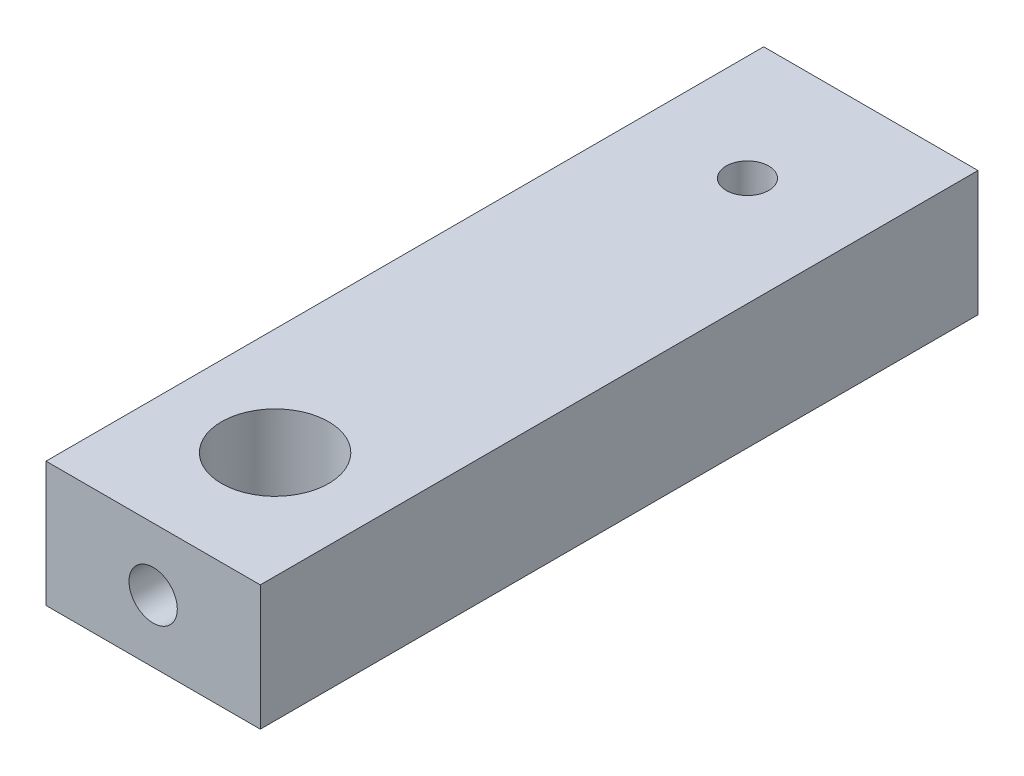
SolidWorks part; units mm, degrees
ref_plane "Front" through (0, 0, 0) normal (0, 0, 1) x (1, 0, 0)
ref_plane "Top" through (0, 0, 0) normal (0, 1, 0) x (1, 0, 0)
ref_plane "Right" through (0, 0, 0) normal (1, 0, 0) x (0, 0, -1)
sketch "Sketch9" plane through (0, 0, 0) normal (0, 1, 0) x (1, 0, 0)
  line L1 (-6, -20.095) -> (6, -20.095)
  line L2 (-6, -20.095) -> (-6, 20.095)
  line L3 (-6, 20.095) -> (6, 20.095)
  line L4 (6, -20.095) -> (6, 20.095)
  line L5 (-6, -20.095) -> (6, 20.095) construction
  line L6 (-6, 20.095) -> (6, -20.095) construction
  point P0 (0, 0)
  dimension "D1" = 12
  dimension "D2" = 40.19
extrude "Extrude3" add sketch "Sketch9" along normal blind 7
hole_wizard "3/32 (0.09375) Diameter Hole1" positions "3DSketch1" profile "Sketch10" hole size "3/32" standard "Ansi Inch"
sketch3d "3DSketch1"
  point P0 (-0.0811, 7, -13.2663)
  dimension "D1" = 15
sketch "Sketch10" plane through (-0.0811, 7, -13.2663) normal (1, 0, 0) x (0, 0, 1)
  line L0 (0, 0) -> (0, 10.7154)
  line L1 (0, 10.7154) -> (1.1906, 10)
  line L2 (1.1906, 10) -> (1.1906, 0)
  line L5 (1.1906, 0) -> (0, 0)
  line L10 (0, 10.7154) -> (-1.1906, 10) construction
  line L11 (0, -6.35) -> (0, 107.95) construction
  dimension "Hole Dia." = 2.3812
  dimension "Hole Depth" = 10
  dimension "Drill Angle" = 118
hole_wizard "Ø6.0 (6) Diameter Hole1" positions "3DSketch2" profile "Sketch11" hole size "Ø6.0" standard "Ansi Metric"
sketch3d "3DSketch2"
  point P0 (0, 7, 13.2665)
  dimension "D1" = 15
sketch "Sketch11" plane through (0, 7, 13.2665) normal (1, 0, 0) x (0, 0, 1)
  line L0 (0, 0) -> (0, 11.8026)
  line L1 (0, 11.8026) -> (3, 10)
  line L2 (3, 10) -> (3, 0)
  line L5 (3, 0) -> (0, 0)
  line L10 (0, 11.8026) -> (-3, 10) construction
  line L11 (0, -6.35) -> (0, 107.95) construction
  dimension "Hole Dia." = 6
  dimension "Hole Depth" = 10
  dimension "Drill Angle" = 118
hole_wizard "#6-32 Tapped Hole2" positions "3DSketch3" profile "Sketch12" tap size "#6-32" standard "Ansi Inch"
sketch3d "3DSketch3"
  point P1 (0, 3.5, 20.095)
sketch "Sketch12" plane through (0, 3.5, 20.095) normal (1, 0, 0) x (0, -1, 0)
  line L0 (0, 0) -> (0, 8.7751)
  line L1 (0, 8.7751) -> (1.3525, 7.9624)
  line L2 (1.3525, 7.9624) -> (1.3525, 0)
  line L5 (1.3525, 0) -> (0, 0)
  line L10 (0, 8.7751) -> (-1.3526, 7.9624) construction
  line L11 (0, -6.35) -> (0, 107.95) construction
  dimension "Tap Drill Dia." = 2.7051
  dimension "Tap Drill Depth" = 7.9624
  dimension "Drill Angle" = 118
hole_wizard "#6-32 Tapped Hole1" positions "3DSketch4" profile "Sketch13" tap size "#6-32" standard "Ansi Inch"
sketch3d "3DSketch4"
  point P0 (0, 3.5, -20.095)
sketch "Sketch13" plane through (0, 3.5, -20.095) normal (1, 0, 0) x (0, 1, 0)
  line L0 (0, 0) -> (0, 10.7727)
  line L1 (0, 10.7727) -> (1.3525, 9.96)
  line L2 (1.3525, 9.96) -> (1.3525, 0)
  line L5 (1.3525, 0) -> (0, 0)
  line L10 (0, 10.7727) -> (-1.3526, 9.96) construction
  line L11 (0, -6.35) -> (0, 107.95) construction
  dimension "Tap Drill Dia." = 2.7051
  dimension "Tap Drill Depth" = 9.96
  dimension "Drill Angle" = 118
